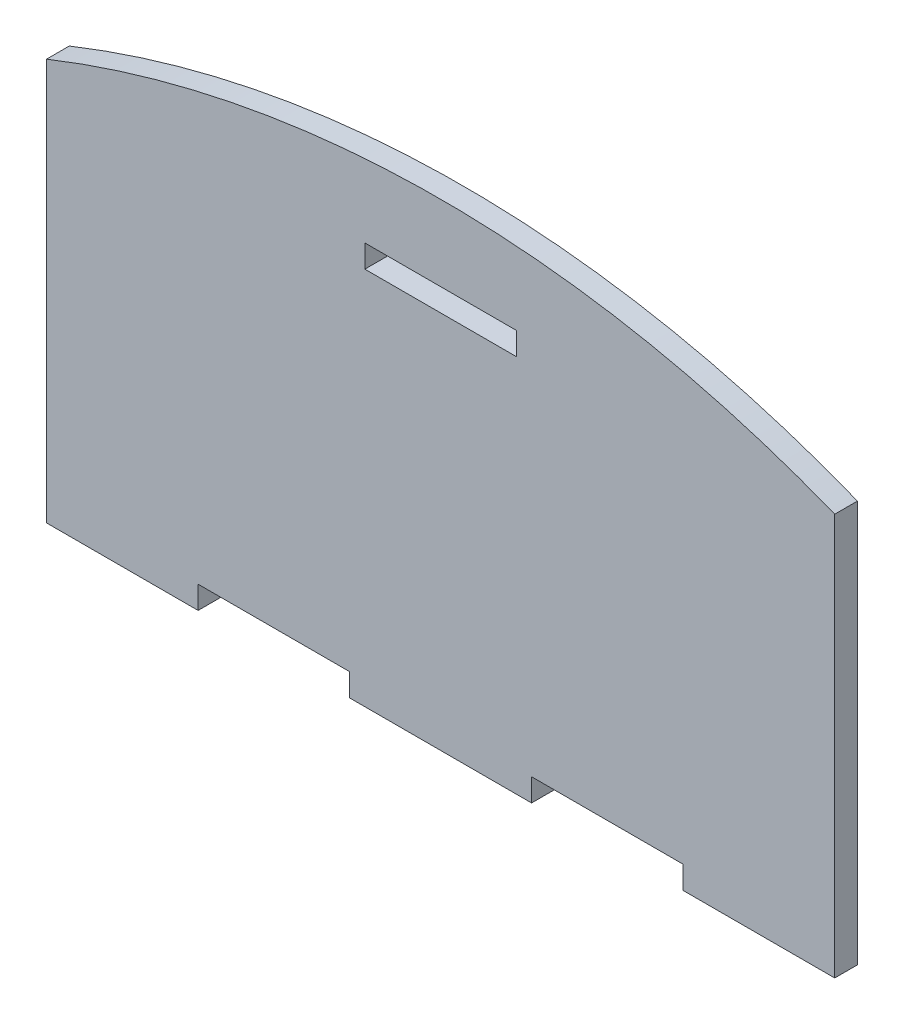
SolidWorks part; units mm, degrees
ref_plane "Front Plane" through (0, 0, 0) normal (0, 0, 1) x (1, 0, 0)
ref_plane "Top Plane" through (0, 0, 0) normal (0, 1, 0) x (1, 0, 0)
ref_plane "Right Plane" through (0, 0, 0) normal (1, 0, 0) x (0, 0, -1)
sketch "Sketch1" plane through (0, 0, 0) normal (0, 0, 1) x (1, 0, 0)
  line L0 (-9.2422, -25.4037) -> (-9.2422, -22.4037)
  line L1 (-29.2422, -25.4037) -> (-9.2422, -25.4037)
  line L2 (74.7578, 27.5963) -> (74.7578, -25.4037)
  line L4 (12.7578, 24.5963) -> (32.7578, 24.5963)
  line L5 (-29.2422, -9.5748) -> (76.1235, 24.9252) construction
  line L6 (-29.2422, 23.6364) -> (59.3185, -47.947) construction
  line L7 (-9.2422, -22.4037) -> (10.7578, -22.4037)
  line L8 (10.7578, -22.4037) -> (10.7578, -25.4037)
  line L9 (34.7578, -25.4037) -> (34.7578, -22.4037)
  line L10 (34.7578, -22.4037) -> (54.7578, -22.4037)
  line L11 (54.7578, -22.4037) -> (54.7578, -25.4037)
  line L12 (10.7578, -25.4037) -> (34.7578, -25.4037)
  line L13 (54.7578, -25.4037) -> (74.7578, -25.4037)
  line L14 (-29.2422, 27.5963) -> (-29.2422, -25.4037)
  line L15 (12.7578, 24.5963) -> (12.7578, 27.5963)
  line L16 (12.7578, 27.5963) -> (32.7578, 27.5963)
  line L17 (32.7578, 24.5963) -> (32.7578, 27.5963)
  line L18 (12.7578, 24.5963) -> (32.7578, 27.5963) construction
  line L19 (12.7578, 27.5963) -> (32.7578, 24.5963) construction
  arc A0 (-29.2422, 27.5963) -> (74.7578, 27.5963) centre (22.7578, -102.6037) cw
  point P0 (0, 0)
  point P18 (22.7578, -25.4037)
  point P19 (22.7578, 26.0963)
  dimension "D1" = 3
  dimension "D2" = 20
  dimension "D3" = 104
  dimension "D4" = 20
  dimension "D5" = 3
  dimension "D6" = 3
  dimension "D7" = 20
  dimension "D8" = 23
  dimension "D9" = 20
  dimension "D10" = 24
  dimension "D11" = 20
  dimension "D12" = 3
  dimension "D13" = 52
extrude "Boss-Extrude1" add sketch "Sketch1" along normal blind 3
